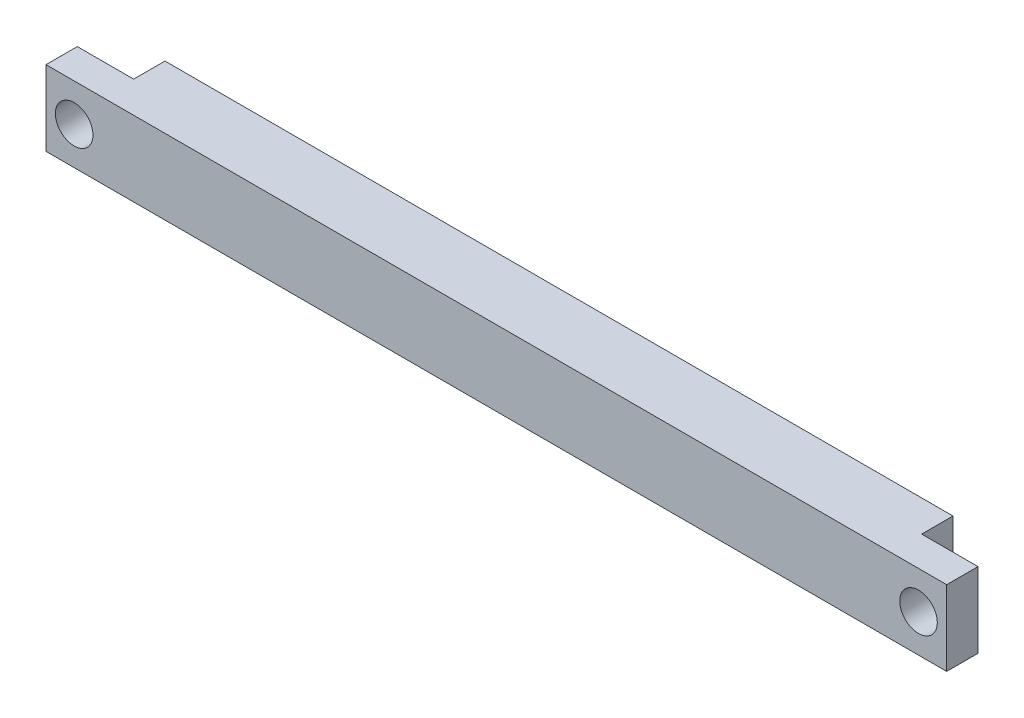
SolidWorks part; units mm, degrees
ref_plane "Front Plane" through (0, 0, 0) normal (0, 0, 1) x (1, 0, 0)
ref_plane "Top Plane" through (0, 0, 0) normal (0, 1, 0) x (1, 0, 0)
ref_plane "Right Plane" through (0, 0, 0) normal (1, 0, 0) x (0, 0, -1)
sketch "Sketch1" plane through (0, 0, 0) normal (0, 0, 1) x (1, 0, 0)
  line L1 (-67.4303, 0) -> (4.5, 0)
  line L2 (-67.4303, 0) -> (-67.4303, 6)
  line L3 (-67.4303, 6) -> (4.5, 6)
  line L4 (4.5, 0) -> (4.5, 6)
extrude "Boss-Extrude1" add sketch "Sketch1" along normal blind 2.5
sketch "Sketch2" plane through (0, 0, 2.5) normal (0, 0, 1) x (1, 0, 0)
  line L0 (4.5, 0) -> (4.5, 6) construction
  line L1 (-67.4303, 0) -> (4.5, 0) construction
  line L2 (-67.4303, 6) -> (-67.4303, 0) construction
  circle A0 centre (2.25, 3) radius 1.5
  circle A1 centre (-65.1803, 3) radius 1.5
  dimension "D1" = 3
  dimension "D3" = 3
  dimension "D4" = 3
  dimension "D2" = 2.25
  dimension "D5" = 2.25
extrude "Cut-Extrude1" cut sketch "Sketch2" against normal blind 2.5
sketch "Sketch3" plane through (0, 0, 0) normal (0, 0, -1) x (-1, 0, 0)
  line L0 (-4.5, 6) -> (67.4303, 6) construction
  line L1 (0, 6) -> (62.9303, 6)
  line L2 (0, 6) -> (0, 0)
  line L3 (0, 0) -> (62.9303, 0)
  line L4 (62.9303, 6) -> (62.9303, 0)
  line L5 (0, 6) -> (0, 0) construction
  line L6 (67.4303, 0) -> (-4.5, 0) construction
  line L7 (62.9303, 0) -> (62.9303, 6) construction
extrude "Boss-Extrude2" add sketch "Sketch3" along normal blind 2.5
